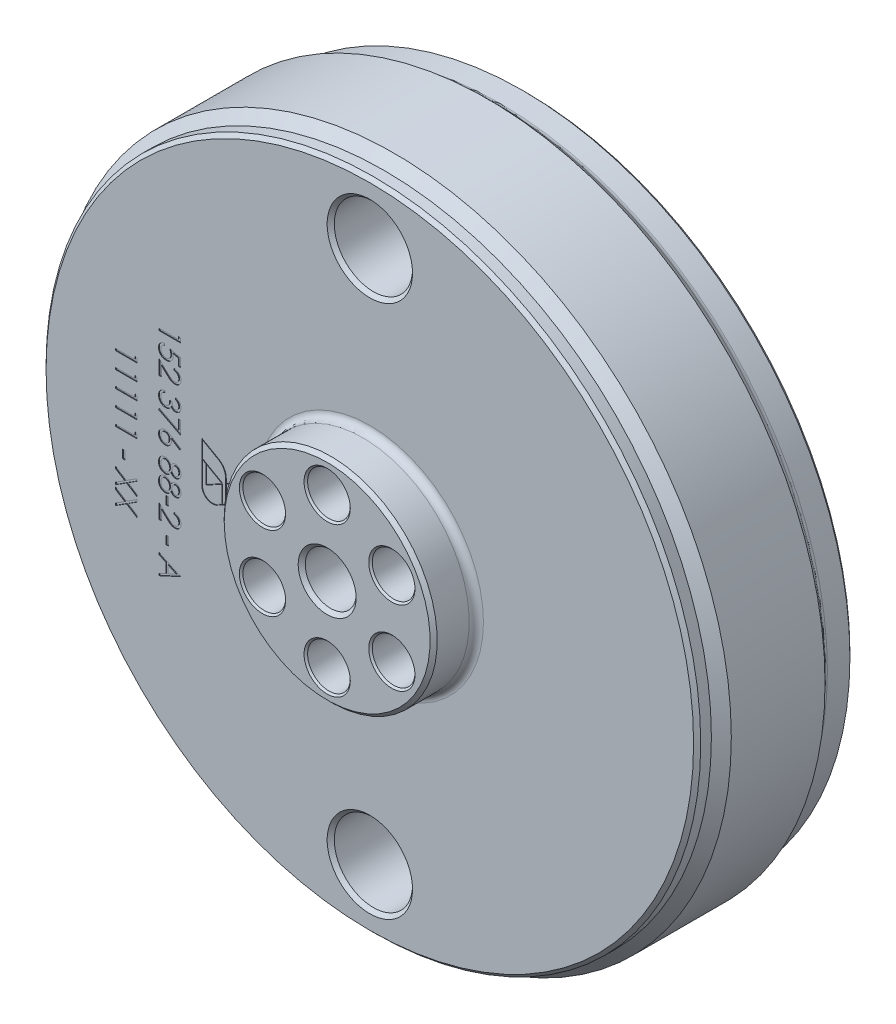
SolidWorks part; units mm, degrees
material "4140 H-T"
ref_plane "Front Plane" through (0, 0, 0) normal (0, 0, 1) x (1, 0, 0)
ref_plane "Top Plane" through (0, 0, 0) normal (0, 1, 0) x (1, 0, 0)
ref_plane "Right Plane" through (0, 0, 0) normal (1, 0, 0) x (0, 0, -1)
sketch "Sketch1" plane through (0, 0, 0) normal (1, 0, 0) x (0, 0, -1)
  line L0 (0, 36.85) -> (0, 45.525)
  line L1 (-0.5, 46.025) -> (-3.6686, 46.025)
  line L2 (-8.2, 6.075) -> (-10.7, 3.575)
  line L4 (-4.2343, 46.2593) -> (-5.4, 47.425)
  line L5 (-5.4, 47.425) -> (-18.58, 47.425)
  line L6 (-18.58, 47.425) -> (-19.98, 46.025)
  line L8 (-27.48, 3.575) -> (-10.7, 3.575)
  line L10 (-27.98, 4.075) -> (-27.48, 3.575)
  line L13 (-19.98, 46.025) -> (-21.48, 46.025)
  line L14 (-21.98, 45.525) -> (-21.98, 15.975)
  line L15 (-22.98, 14.975) -> (-27.48, 14.975)
  line L20 (-27.48, 14.975) -> (-27.98, 14.475)
  line L21 (-27.98, 14.475) -> (-27.98, 4.075)
  line L26 (0, 0) -> (-52.2303, 0) construction
  line L27 (-8.2, 6.075) -> (-8.2, 24.1079)
  line L30 (-21.48, 46.025) -> (-21.98, 45.525)
  line L32 (0, 45.525) -> (-0.5, 46.025)
  arc A0 (-8.2, 24.1079) -> (-1.1714, 35.0297) centre (3.8, 24.1079) cw
  arc A1 (-22.98, 14.975) -> (-21.98, 15.975) centre (-22.98, 15.975) ccw
  arc A5 (-4.2343, 46.2593) -> (-3.6686, 46.025) centre (-3.6686, 46.825) ccw
  arc A6 (0, 36.85) -> (-1.1714, 35.0297) centre (-2, 36.85) cw
  point P1 (0, 46.025)
  point P15 (-21.98, 46.025)
  point P23 (-27.98, 3.575)
  point P44 (-4, 46.025)
  dimension "D32" = 2
  dimension "D34" = 21.98
  dimension "D9" = 12
  dimension "D11" = 1
  dimension "D14" = 0.8
  dimension "D5" = 2.5
  dimension "D1" = 94.85
  dimension "D4" = 7.15
  dimension "D6" = 45
  dimension "D7" = 92.05
  dimension "D8" = 8.2
  dimension "D10" = 6
  dimension "D12" = 29.95
  dimension "D13" = 2
  dimension "D18" = 0.5
  dimension "D20" = 0.5
  dimension "D21" = 92.05
  dimension "D22" = 45
  dimension "D26" = 4
  dimension "D29" = 45
  dimension "D33" = 73.7
  dimension "D36" = 45
revolve "Revolve1" add sketch "Sketch1" angle 360 about L26
cosmetic thread "Cosmetic Thread1" parameters "D2"=93
sketch "Sketch15" plane through (0, 0, 21.98) normal (0, 0, 1) x (1, 0, 0)
  line L0 (0, 0) -> (70.0011, 0) construction
  circle A0 centre (0, 0) radius 37.5 construction
  point P4 (37.5, 0)
  point P8 (0, -37.5)
  point P9 (-37.5, 0)
  point P10 (0, 37.5)
  dimension "D1" = 75
  dimension "D2" = 4
hole_wizard "Ø11.0 (11) Diameter Hole1" positions "Sketch17" profile "Sketch16" hole size "Ø11.0" standard "Ansi Metric"
sketch "Sketch17" plane through (0, 0, 21.98) normal (0, 0, 1) x (1, 0, 0)
  point P2 (0, -37.5)
  point P6 (0, 37.5)
sketch "Sketch16" plane through (0, -37.5, 21.98) normal (1, 0, 0) x (0, -1, 0)
  line L0 (0, 0) -> (0, 13.3047)
  line L1 (0, 13.3047) -> (5.5, 10)
  line L2 (5.5, 10) -> (5.5, 0.5)
  line L3 (5.5, 0.5) -> (6, 0)
  line L5 (6, 0) -> (0, 0)
  line L6 (-5.5, 0.5) -> (-6, 0) construction
  line L10 (0, 13.3047) -> (-5.5, 10) construction
  line L11 (0, -6.35) -> (0, 107.95) construction
  dimension "Hole Dia." = 11
  dimension "Hole Depth" = 10
  dimension "Near C'Sink Dia." = 12
  dimension "Near C'Sink Angle" = 90
  dimension "Drill Angle" = 118
sketch "Sketch19" plane through (0, 0, 27.98) normal (0, 0, 1) x (1, 0, 0)
  circle A0 centre (0, 0) radius 10.5 construction
  point P3 (0, 10.5)
  dimension "D1" = 21
hole_wizard "Ø6.0 (6) Diameter Hole1" positions "Sketch23" profile "Sketch22" hole size "Ø6.0" standard "Ansi Metric" end condition through all
sketch "Sketch23" plane through (0, 0, 27.98) normal (0, 0, 1) x (1, 0, 0)
  point P0 (0, 10.5)
sketch "Sketch22" plane through (0, 10.5, 27.98) normal (1, 0, 0) x (0, -1, 0)
  line L0 (0, 0) -> (0, 19.78)
  line L1 (0, 19.78) -> (3.25, 19.78)
  line L2 (3, 19.53) -> (3, 0.25)
  line L3 (3, 0.25) -> (3.25, 0)
  line L5 (3.25, 0) -> (0, 0)
  line L6 (-3, 0.25) -> (-3.25, 0) construction
  line L7 (3.25, 19.78) -> (3, 19.53)
  line L8 (-3.25, 19.78) -> (-3, 19.53) construction
  line L11 (0, -6.35) -> (0, 107.95) construction
  dimension "Thru Hole Dia." = 6
  dimension "Thru Hole Depth" = 19.78
  dimension "Near C'Sink Dia." = 6.5
  dimension "Near C'Sink Angle" = 90
  dimension "Far C'Sink Dia." = 6.5
  dimension "Far C'Sink Angle" = 90
pattern_circular "CirPattern1" count 6 over 360 about axis through (0, 0, 0) along (0, 0, 1) of "Ø6.0 (6) Diameter Hole1"
sketch "Sketch18" plane through (0, 0, 21.98) normal (0, 0, 1) x (1, 0, 0)
  line L0 (0, 0) -> (-74.7152, 0) construction
  line L1 (0, 0) -> (0, -71.1316) construction
  line L2 (0, 0) -> (82.8113, 0) construction
  line L3 (0, 0) -> (-36.8618, -25.8109) construction
  line L4 (-23.6288, 22.5105) -> (-23.6288, -25.8109) construction
  arc A1 (-45, 0) -> (-36.8618, -25.8109) centre (0, 0) ccw construction
  text T0 "\r\n152 376 88-2 - A\r\n11111 - XX" font "Century Gothic" height 3
  line B0 (-23.6288, -3.1583) -> (-23.6288, 0.1101)
  line B1 (-22.9625, -2.6742) -> (-22.9625, -0.2687)
  line B2 (-23.5288, 0.0533) -> (-23.0625, -0.2119)
  line B3 (-20.1846, -1.1478) -> (-20.1846, -0.5778)
  line B4 (-17.9207, 0.1101) -> (-20.1846, -1.1478)
  line B5 (-22.9625, -2.6742) -> (-20.8153, -1.4897)
  line B6 (-20.8153, -4.1191) -> (-21.3317, -4.4179)
  line B7 (-17.9207, -1.4939) -> (-17.9207, 0.1101)
  line B8 (-20.1846, -3.7752) -> (-20.8153, -4.1191)
  line B9 (-20.1846, -3.7752) -> (-18.728, -2.9113)
  line B10 (-23.6288, 0.1101) -> (-23.6288, 2.6076)
  line B11 (-21.1596, 1.2035) -> (-23.6288, 2.6076)
  line B12 (-20.715, -3.9734) -> (-20.2846, -3.7182)
  line B13 (-18.0207, -1.4939) -> (-18.0207, -0.0598)
  line B14 (-18.0207, -0.0598) -> (-20.1846, -1.2622)
  line B15 (-20.2846, -0.5778) -> (-20.2846, -3.7182)
  line B16 (-21.2114, 1.1179) -> (-23.5288, 2.4357)
  line B17 (-23.5288, 0.1683) -> (-23.5288, 2.4357)
  line B18 (-20.715, -1.4317) -> (-20.715, -3.9734)
  line B19 (-23.5288, 0.1683) -> (-20.715, -1.4317)
  line B20 (-20.8153, -4.0036) -> (-21.3837, -4.3324)
  line B21 (-23.5288, -3.1583) -> (-23.5288, 0.0533)
  line B22 (-20.1846, -1.2622) -> (-20.1846, -3.6589)
  line B23 (-20.1846, -3.6589) -> (-18.779, -2.8253)
  line B24 (-23.0625, -2.8435) -> (-23.0625, -0.2119)
  line B25 (-23.0625, -2.8435) -> (-20.8153, -1.6039)
  line B26 (-20.8153, -1.6039) -> (-20.8153, -4.0036)
  line B27 (-22.9625, -0.2687) -> (-20.8153, -1.4897)
  arc B28 (-18.728, -2.9113) -> (-17.9207, -1.4939) centre (-19.5687, -1.4939) ccw
  arc B29 (-23.6288, -3.1583) -> (-21.3317, -4.4179) centre (-22.1349, -3.1583) ccw
  arc B30 (-20.1846, -0.5778) -> (-21.1596, 1.2035) centre (-22.2993, -0.5778) ccw
  arc B31 (-18.779, -2.8253) -> (-18.0207, -1.4939) centre (-19.5687, -1.4939) ccw
  arc B32 (-20.2846, -0.5778) -> (-21.2114, 1.1179) centre (-22.2993, -0.5778) ccw
  arc B33 (-23.5288, -3.1583) -> (-21.3837, -4.3324) centre (-22.1349, -3.1583) ccw
  dimension "D2" = 45
  dimension "D3" = 35
sketch_block_instance "SKETCH LOGO-1"
sketch_block "SKETCH LOGO" parameters "D1"=29.059, "D2"=11.4163, "D3"=29.624, "D4"=6.8884
extrude "Cut-Extrude1" cut sketch "Sketch18" against normal blind 0.1
